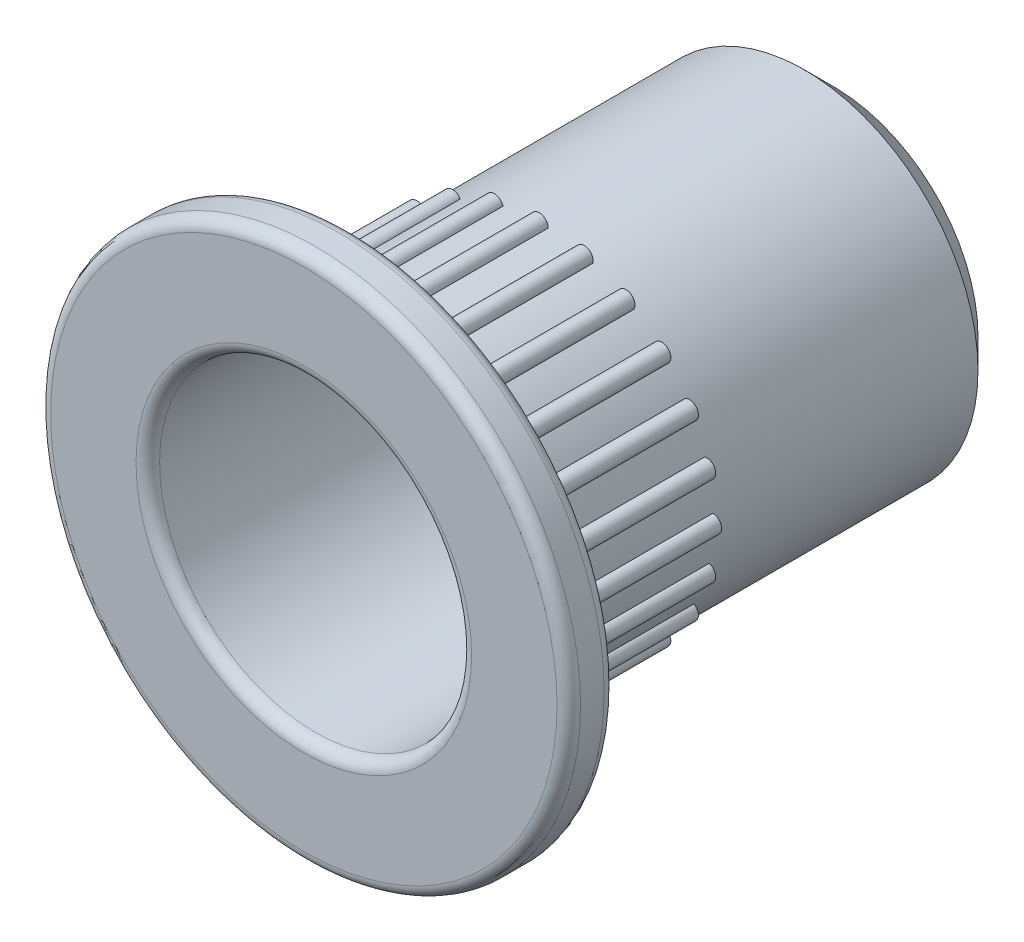
SolidWorks part; units mm, degrees
material "1060 Сплав"
ref_plane "Спереди" through (0, 0, 0) normal (0, 0, 1) x (1, 0, 0)
ref_plane "Сверху" through (0, 0, 0) normal (0, 1, 0) x (1, 0, 0)
ref_plane "Справа" through (0, 0, 0) normal (1, 0, 0) x (0, 0, -1)
sketch "Эскиз1" plane through (0, 0, 0) normal (0, 0, 1) x (1, 0, 0)
  circle A0 centre (0, 0) radius 2.95
  dimension "D1" = 5.9
extrude "Вытянуть1" add sketch "Эскиз1" along normal blind 9
sketch "Эскиз2" plane through (0, 0, 9) normal (0, 0, 1) x (1, 0, 0)
  circle A0 centre (0, 0) radius 2.6
  circle A1 centre (0, 0) radius 4.5
  dimension "D1" = 5.2
  dimension "D2" = 9
extrude "Вытянуть2" add sketch "Эскиз2" against normal blind 0.8
sketch "Эскиз3" plane through (0, 0, 9) normal (0, 0, 1) x (1, 0, 0)
  circle A0 centre (0, 0) radius 2
  dimension "D1" = 4
extrude "Вырез-Вытянуть1" cut sketch "Эскиз3" against normal through all
ref_plane "Плоскость1" through (0, 0, 5) normal (0, 0, 1) x (1, 0, 0)
sketch "Эскиз4" plane through (0, 0, 5) normal (0, 0, 1) x (1, 0, 0)
  line L0 (0.15, 2.9462) -> (-0.15, 2.9462)
  line L1 (0, 0) -> (0, 0.6061) construction
  circle A0 centre (0, 0) radius 2.95 construction
  arc A2 (-0.15, 2.9462) -> (0.15, 2.9462) centre (0, 2.9462) cw
  dimension "D1" = 0.3
extrude "Вытянуть3" add sketch "Эскиз4" along normal up to next
pattern_circular "Круговой массив1" count 24 every 15 about axis through (0, 0, 0) along (0, 0, 1) of "Вытянуть3"
chamfer "Фаска2" distance 0.5 distance2 0.5 1 edges at (2.95, 0, 0)
fillet "Скругление1" radius 0.2 2 edges at (4.5, 0, 8.2) (4.5, 0, 9)
sketch "Эскиз6" plane through (0, 0, 9) normal (0, 0, 1) x (1, 0, 0)
  circle A0 centre (0, 0) radius 2
  circle A1 centre (0, 0) radius 2 construction
  circle A2 centre (0, 0) radius 2.65
  dimension "D1" = 5.3
extrude "Вырез-Вытянуть2" cut sketch "Эскиз6" against normal blind 4
fillet "Скругление2" radius 0.2 1 edges at (2.65, 0, 9)
